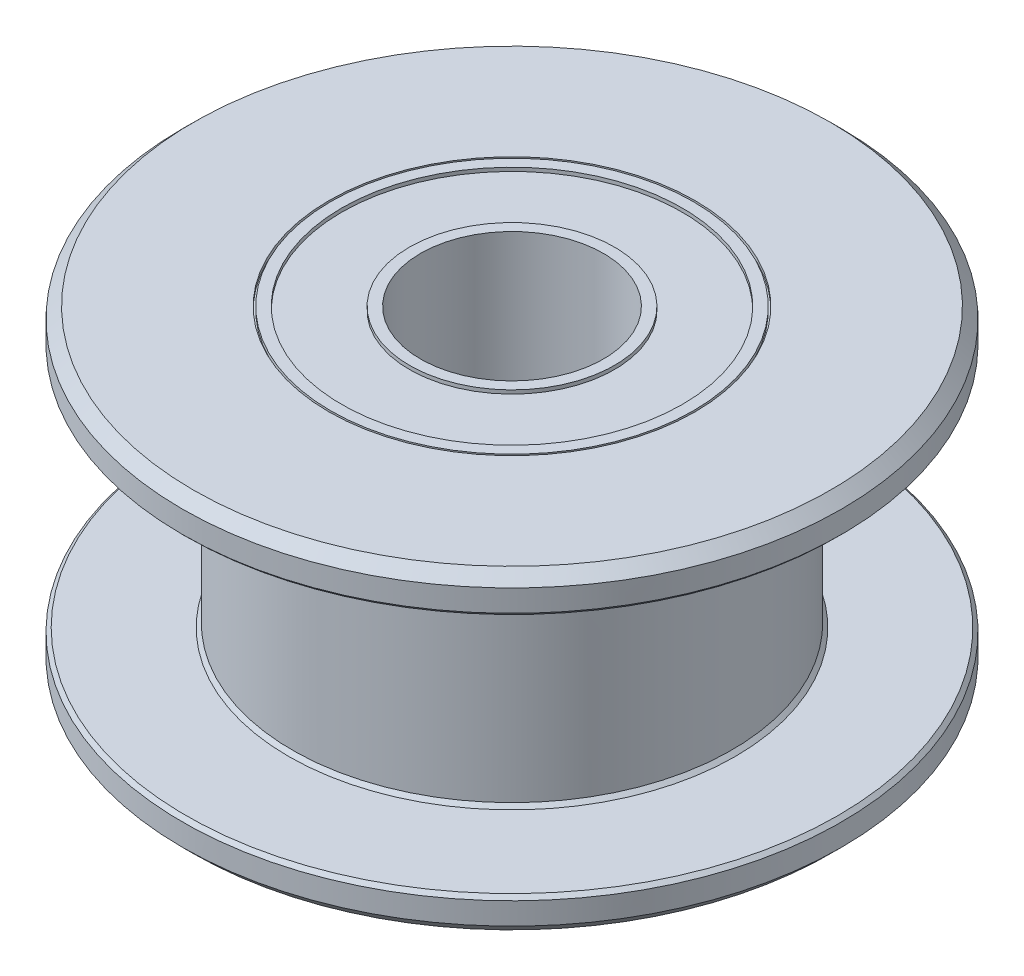
SolidWorks part; units mm, degrees
ref_plane "Alzado" through (0, 0, 0) normal (0, 0, 1) x (1, 0, 0)
ref_plane "Planta" through (0, 0, 0) normal (0, 1, 0) x (1, 0, 0)
ref_plane "Vista lateral" through (0, 0, 0) normal (1, 0, 0) x (0, 0, -1)
sketch "Croquis1" plane through (0, 0, 0) normal (0, 0, 1) x (1, 0, 0)
  line L0 (6.5, -20.7507) -> (2.5, -20.7507)
  line L1 (2.5, -20.7507) -> (2.5, -20.8507)
  line L2 (-2.5, -20.7507) -> (-2.5, -37.2697) construction
  line L3 (2.5, -20.8507) -> (2.45, -20.8507)
  line L4 (6.5, -20.7507) -> (6.5, -21.7507)
  line L5 (6.5, -21.7507) -> (3.5, -21.7507)
  line L6 (3.5, -21.7507) -> (3.5, -28.3507)
  line L7 (3.5, -28.3507) -> (6.5, -28.3507)
  line L8 (6.5, -29.3507) -> (1.6902, -29.3507)
  line L9 (6.5, -28.3507) -> (6.5, -29.3507)
  line L10 (0, -20.8507) -> (0, -29.2507)
  line L11 (0, -29.2507) -> (1.6902, -29.2507)
  line L12 (1.6902, -29.2507) -> (1.6902, -29.3507)
  line L13 (2.15, -20.8507) -> (0.3, -20.8507)
  line L15 (0, -20.8507) -> (0, -20.7507)
  line L16 (0, -20.7507) -> (0.3, -20.7507)
  line L17 (0.3, -20.8507) -> (0.3, -20.7507)
  line L19 (2.45, -20.8507) -> (2.45, -20.7507)
  line L20 (2.45, -20.7507) -> (2.15, -20.7507)
  line L21 (2.15, -20.8507) -> (2.15, -20.7507)
  point P0 (6.5, -21.2507)
  dimension "D1" = 9
  dimension "D2" = 6
  dimension "D3" = 9
  dimension "D4" = 1
  dimension "D5" = 1
  dimension "D6" = 8.6
  dimension "D7" = 0.1
  dimension "D8" = 0.1
  dimension "D9" = 2.5
  dimension "D10" = 4
  dimension "D11" = 0.3
  dimension "D12" = 0.3
  dimension "D13" = 0.05
revolve "Revolución3" add sketch "Croquis1" angle 360 about L2
chamfer "Chaflán3" distance 0.3 angle 45 2 edges at (-11.5, -29.3507, 0) (-11.5, -20.7507, 0)
chamfer "Chaflán4" distance 0.1 angle 45 3 edges at (-11.5, -28.3507, 0) (-8.5, -28.3507, 0) (-11.5, -21.7507, 0)
